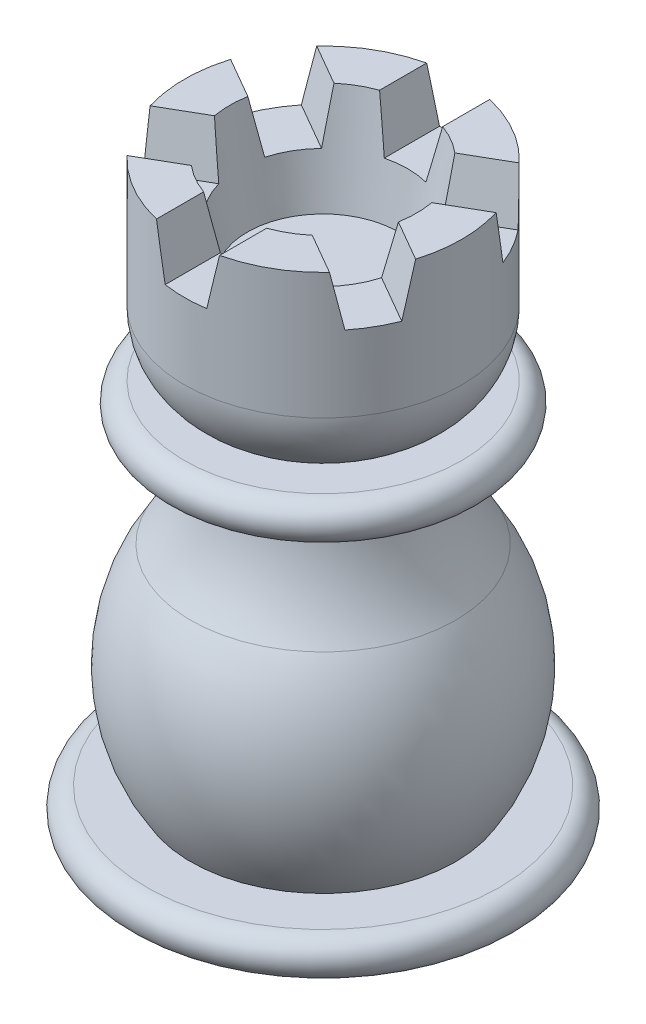
SolidWorks part; units mm, degrees
ref_plane "Front Plane" through (0, 0, 0) normal (0, 0, 1) x (1, 0, 0)
ref_plane "Top Plane" through (0, 0, 0) normal (0, 1, 0) x (1, 0, 0)
ref_plane "Right Plane" through (0, 0, 0) normal (1, 0, 0) x (0, 0, -1)
sketch "Sketch1" plane through (0, 0, 0) normal (0, 0, 1) x (1, 0, 0)
  line L0 (0, 0) -> (0, 4.913) construction
  line L1 (0, 0) -> (14, 0)
  line L2 (14, 3) -> (10.5, 3)
  line L3 (8, 27.8038) -> (11, 27.8038)
  line L4 (11, 30.8038) -> (8, 30.8038)
  line L5 (11, 36) -> (11, 46)
  line L6 (11, 46) -> (0, 46)
  line L7 (0, 0) -> (0, 46)
  arc A0 (14, 0) -> (14, 3) centre (14, 1.5) ccw
  arc A1 (10.5, 3) -> (10.4999, 19.5833) centre (-2, 11.2916) ccw
  arc A2 (10.4999, 19.5833) -> (8, 27.8038) centre (22.9998, 27.8749) cw
  arc A3 (11, 27.8038) -> (11, 30.8038) centre (11, 29.3038) ccw
  arc A4 (8, 30.8038) -> (11, 36) centre (5, 36) ccw
  point P14 (13, 11.2916)
  dimension "D1" = 1.5
  dimension "D4" = 15
  dimension "D5" = 15
  dimension "D6" = 13
  dimension "D8" = 1.5
  dimension "D9" = 6
  dimension "D2" = 14
  dimension "D3" = 10.5
  dimension "D7" = 8
  dimension "D10" = 46
  dimension "D11" = 10
  dimension "D12" = 11
revolve "Revolve1" add sketch "Sketch1" angle 360 about L0
sketch "Sketch3" plane through (0, 46, 0) normal (0, 1, 0) x (1, 0, 0)
  circle A0 centre (0, 0) radius 6
  dimension "D1" = 12
extrude "Cut-Extrude1" cut sketch "Sketch3" against normal blind 8
sketch "Sketch4" plane through (0, 0, 0) normal (0, 0, 1) x (1, 0, 0)
  line L0 (0, 49.6503) -> (0, 38.6487) construction
  line L1 (6, 38) -> (7.4106, 46)
  line L2 (7.4106, 46) -> (6, 46)
  line L3 (6, 46) -> (6, 38)
  line L4 (11, 46) -> (-11, 46) construction
  point P5 (7.3227, 49.8828)
  point P9 (7.6931, 47.6019)
  point P10 (0, 0)
  dimension "D1" = 10
  dimension "D2" = 6
  dimension "D3" = 8
revolve "Cut-Revolve1" cut sketch "Sketch4" angle 360 about L0
sketch "Sketch5" plane through (0, 0, 0) normal (0, 0, 1) x (1, 0, 0)
  line L0 (0, 0) -> (0, 66.4678) construction
  line L1 (-14, 0) -> (14, 0) construction
  line L2 (-2.5, 46) -> (-1.6498, 42)
  line L3 (11, 46) -> (-11, 46) construction
  line L4 (-1.6498, 42) -> (1.6498, 42)
  line L5 (1.6498, 42) -> (2.5, 46)
  line L6 (-2.5, 46) -> (2.5, 46)
  dimension "D1" = 5
  dimension "D2" = 4
  dimension "D3" = 24
extrude "Cut-Extrude2" cut sketch "Sketch5" against normal through all both and the other way through all
pattern_circular "CirPattern2" count 3 over 360 about axis through (0, 0, 0) along (0, 1, 0) of "Cut-Extrude2"
